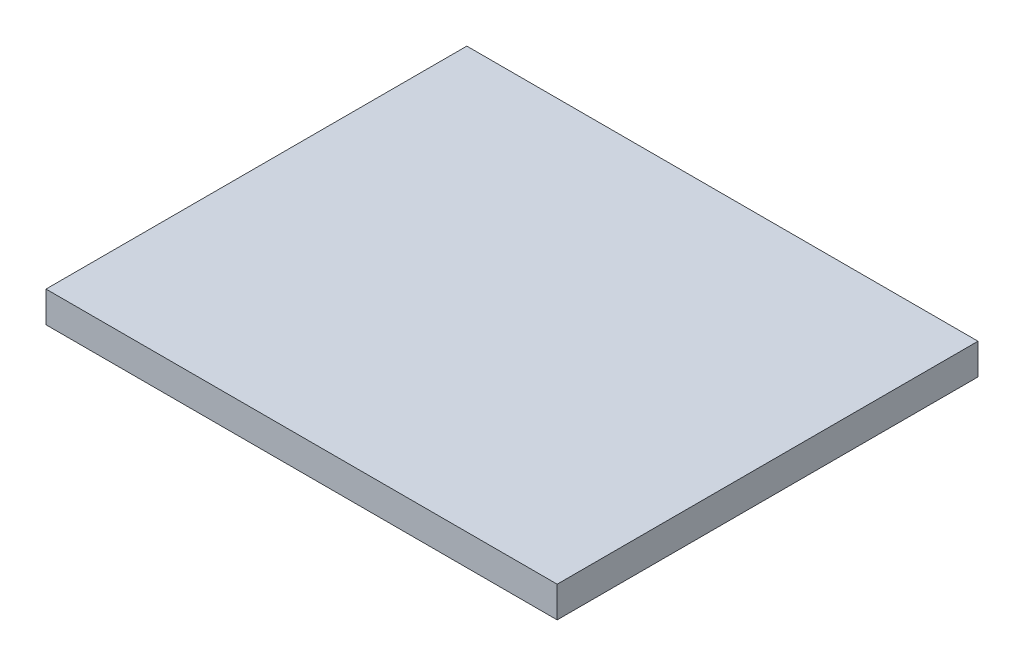
SolidWorks part; units mm, degrees
ref_plane "Front Plane" through (0, 0, 0) normal (0, 0, 1) x (1, 0, 0)
ref_plane "Top Plane" through (0, 0, 0) normal (0, 1, 0) x (1, 0, 0)
ref_plane "Right Plane" through (0, 0, 0) normal (1, 0, 0) x (0, 0, -1)
sketch "Sketch1" plane through (0, 0, 0) normal (0, 1, 0) x (1, 0, 0)
  line L1 (-206.5, -170) -> (206.5, -170)
  line L2 (-206.5, -170) -> (-206.5, 170)
  line L3 (-206.5, 170) -> (206.5, 170)
  line L4 (206.5, -170) -> (206.5, 170)
  line L5 (-206.5, -170) -> (206.5, 170) construction
  line L6 (-206.5, 170) -> (206.5, -170) construction
  point P0 (0, 0)
  dimension "D1" = 413
  dimension "D2" = 340
extrude "Boss-Extrude1" add sketch "Sketch1" along normal blind 25
